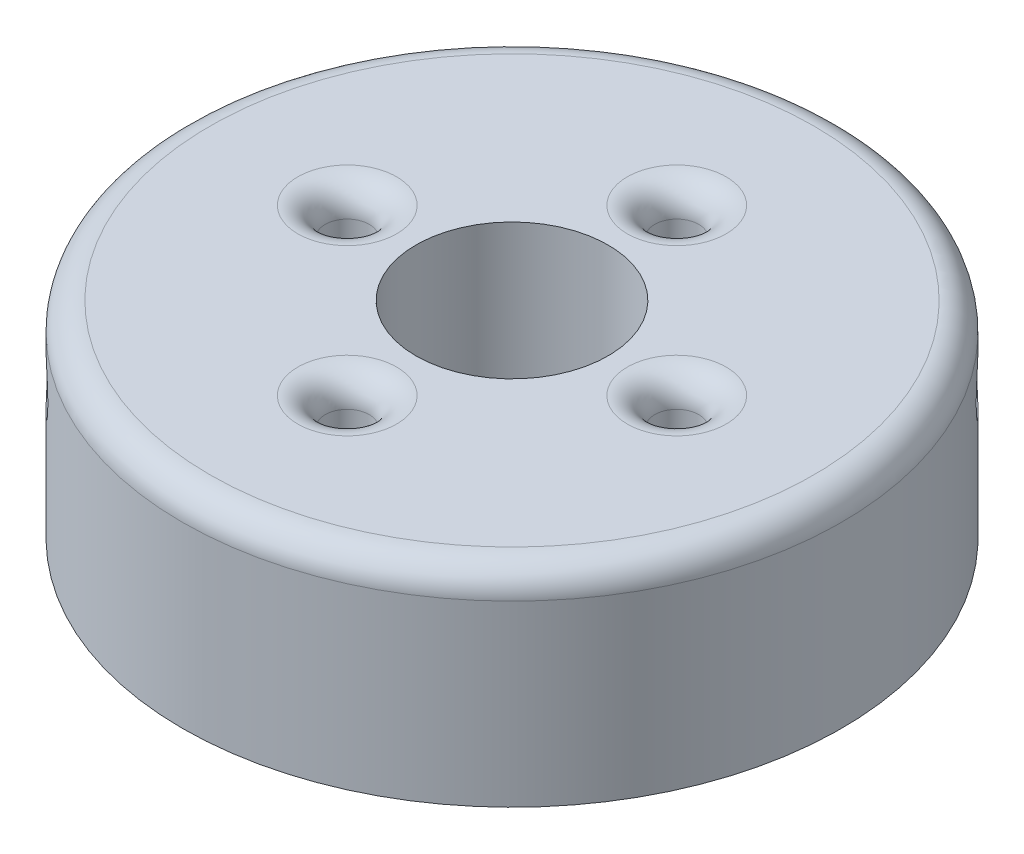
SolidWorks part; units mm, degrees
ref_plane "Front Plane" through (0, 0, 0) normal (0, 0, 1) x (1, 0, 0)
ref_plane "Top Plane" through (0, 0, 0) normal (0, 1, 0) x (1, 0, 0)
ref_plane "Right Plane" through (0, 0, 0) normal (1, 0, 0) x (0, 0, -1)
sketch "Sketch1" plane through (0, 0, 0) normal (0, 1, 0) x (1, 0, 0)
  circle A0 centre (0, 0) radius 7
  circle A1 centre (0, 0) radius 24
  circle A3 centre (0, 12) radius 1.6
  circle A4 centre (12, 0) radius 1.6
  circle A5 centre (0, -12) radius 1.6
  circle A6 centre (-12, 0) radius 1.6
  point P15 (0, 0)
  dimension "D1" = 4
extrude "Boss-Extrude1" add sketch "Sketch1" along normal blind 15
sketch "Sketch3" plane through (0, 15, 0) normal (0, 1, 0) x (1, 0, 0)
  line L1 (16.9706, 16.9706) -> (25.4558, 8.4853)
  line L2 (25.4558, 8.4853) -> (23.1822, 6.2117)
  circle A0 centre (0, 0) radius 24 construction
  arc A1 (23.1822, 6.2117) -> (16.9706, 16.9706) centre (0, 0) ccw
extrude "Boss-Extrude2" add sketch "Sketch3" against normal blind 16
sketch "Sketch4" plane through (16.9706, 0, -16.9706) normal (0.7071, 0, -0.7071) x (-0.7071, 0, -0.7071)
  line L0 (0, 0) -> (0, 10)
  line L1 (0, 15) -> (0, 0) construction
  circle A0 centre (0, 10) radius 2.1
  line M5 (0, 0) -> (0, 15)
extrude "Cut-Extrude1" cut sketch "Sketch4" against normal blind 72 contours L0 A0 M5 | A0 L0 M5
sketch "Sketch5" plane through (0, 15, 0) normal (0, 1, 0) x (1, 0, 0)
  line L0 (23.1822, 6.2117) -> (25.4558, 8.4853)
  line L1 (25.4558, 8.4853) -> (16.9706, 16.9706)
  arc A0 (23.1822, 6.2117) -> (16.9706, 16.9706) centre (0, 0) ccw
extrude "Cut-Extrude2" cut sketch "Sketch5" against normal blind 72
fillet "Fillet3" radius 2 5 edges at (-12, 15, 1.6) (0, 15, 13.6) (12, 15, 1.6) (0, 15, -10.4) (0, 15, 24)
